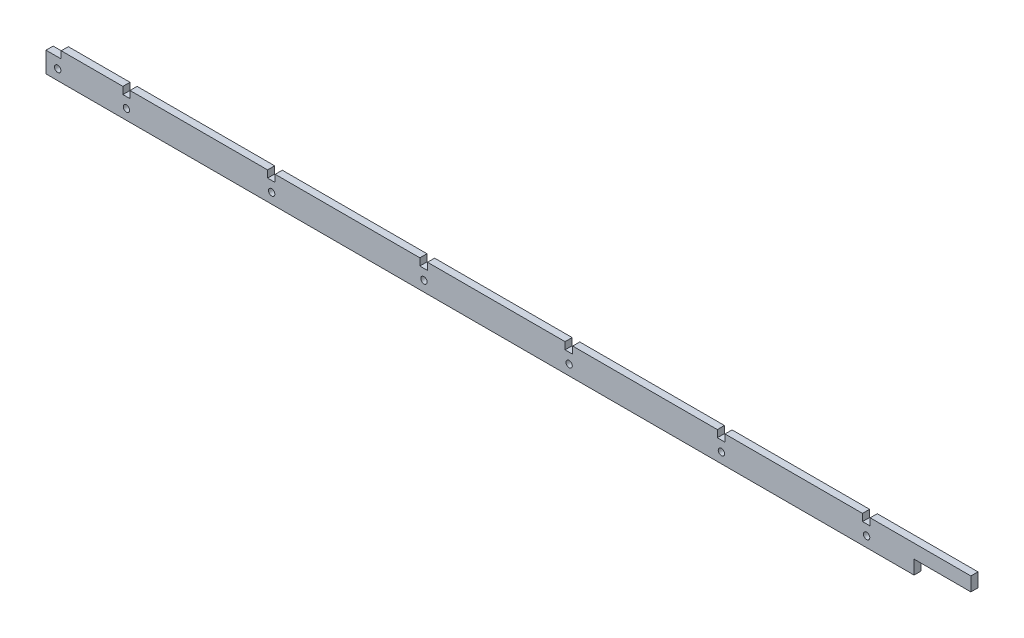
SolidWorks part; units mm, degrees
ref_plane "Front Plane" through (0, 0, 0) normal (0, 0, 1) x (1, 0, 0)
ref_plane "Top Plane" through (0, 0, 0) normal (0, 1, 0) x (1, 0, 0)
ref_plane "Right Plane" through (0, 0, 0) normal (1, 0, 0) x (0, 0, -1)
sketch "Sketch1" plane through (0, 0, 0) normal (0, 0, 1) x (1, 0, 0)
  line L0 (5915.0819, 2730.7757) -> (5915.0819, 2727.6007)
  line L1 (6007.303, 2730.7757) -> (6007.303, 2727.6007)
  line L2 (6010.7066, 2730.7757) -> (6010.7066, 2727.6007)
  line L3 (6075.3623, 2730.7757) -> (6075.3623, 2727.6007)
  line L4 (6078.7659, 2730.7757) -> (6078.7659, 2727.6007)
  line L5 (6140.2466, 2730.7757) -> (6140.2466, 2727.6007)
  line L6 (6143.6502, 2730.7757) -> (6143.6502, 2727.6007)
  line L7 (6208.3059, 2730.7757) -> (6208.3059, 2727.6007)
  line L8 (6211.7095, 2730.7757) -> (6211.7095, 2727.6007)
  line L9 (6273.1902, 2730.7757) -> (6273.1902, 2727.6007)
  line L10 (6276.5938, 2730.7757) -> (6276.5938, 2727.6007)
  line L11 (6276.5938, 2727.6007) -> (6273.1902, 2727.6007)
  line L12 (6211.7095, 2727.6007) -> (6208.3059, 2727.6007)
  line L13 (6143.6502, 2727.6007) -> (6140.2466, 2727.6007)
  line L14 (6078.7659, 2727.6007) -> (6075.3623, 2727.6007)
  line L15 (6010.7066, 2727.6007) -> (6007.303, 2727.6007)
  line L16 (5945.8223, 2727.6007) -> (5942.6473, 2727.6007)
  line L17 (5915.0819, 2727.6007) -> (5908.2747, 2727.6007)
  line L18 (6321.6216, 2730.7757) -> (6276.5938, 2730.7757)
  line L19 (6273.1902, 2730.7757) -> (6211.7095, 2730.7757)
  line L20 (6208.3059, 2730.7757) -> (6143.6502, 2730.7757)
  line L21 (6140.2466, 2730.7757) -> (6078.7659, 2730.7757)
  line L22 (6075.3623, 2730.7757) -> (6010.7066, 2730.7757)
  line L23 (6007.303, 2730.7757) -> (5945.8223, 2730.7757)
  line L24 (5942.6473, 2730.7757) -> (5915.0819, 2730.7757)
  line L25 (6296.2216, 2718.4059) -> (5908.2747, 2718.4059)
  line L26 (5945.8223, 2730.7757) -> (5945.8223, 2727.6007)
  line L27 (5942.6473, 2730.7757) -> (5942.6473, 2727.6007)
  line L28 (5908.2747, 2718.4059) -> (5908.2747, 2727.6007)
  line L29 (6296.2216, 2724.5908) -> (6296.2216, 2718.4059)
  line L30 (6321.6216, 2730.7757) -> (6321.6216, 2724.5908)
  line L31 (6296.2216, 2724.5908) -> (6321.6216, 2724.5908)
  circle A0 centre (5944.2348, 2723.0033) radius 1.4224
  circle A1 centre (6009.1191, 2723.0033) radius 1.4224
  circle A2 centre (6077.1784, 2723.0033) radius 1.4224
  circle A3 centre (6142.0627, 2723.0033) radius 1.4224
  circle A4 centre (6210.122, 2723.0033) radius 1.4224
  circle A5 centre (6275.0063, 2723.0033) radius 1.4224
  circle A6 centre (5913.4944, 2723.0033) radius 1.4224
extrude "Boss-Extrude1" add sketch "Sketch1" along normal blind 3.175
